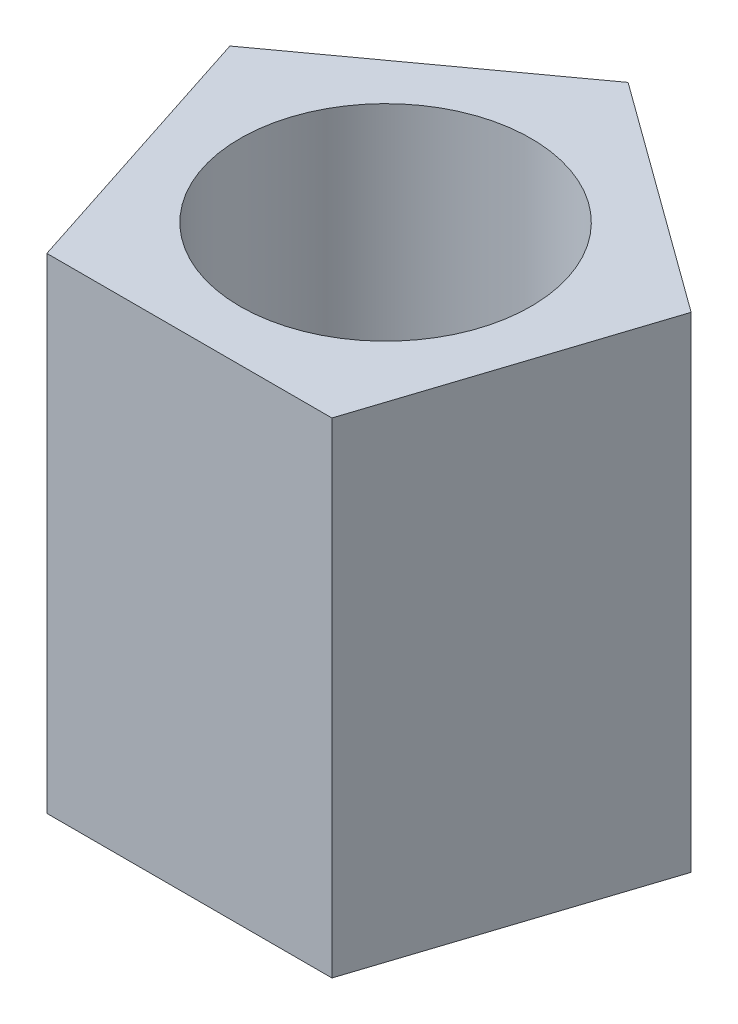
SolidWorks part; units mm, degrees
ref_plane "Front Plane" through (0, 0, 0) normal (0, 0, 1) x (1, 0, 0)
ref_plane "Top Plane" through (0, 0, 0) normal (0, 1, 0) x (1, 0, 0)
ref_plane "Right Plane" through (0, 0, 0) normal (1, 0, 0) x (0, 0, -1)
sketch "Sketch1" plane through (0, 0, 0) normal (0, 1, 0) x (1, 0, 0)
  line L0 (0, 0) -> (0, 6.35) construction
  line L1 (0, 0) -> (6.0392, 1.9623) construction
  line L2 (0, 6.35) -> (6.0392, 1.9623)
  line L3 (0, 6.35) -> (0, 0)
  line L4 (0, 0) -> (6.0392, 1.9623)
  circle A0 centre (0, 0) radius 6.35 construction
  dimension "D2" = 72
sketch "Sketch2" plane through (0, 0, 0) normal (0, 0, 1) x (1, 0, 0)
  line L0 (0, 0) -> (0, 12.7) construction
ref_plane "Plane1" through (0, 12.7, 0) normal (0, 1, 0) x (1, 0, 0)
extrude "Boss-Extrude1" add sketch "Sketch1" along normal up to surface (12.7 mm away) contours L4 L2 L3 up to plane "Plane1"
pattern_circular "CirPattern1" count 5 over 360 about axis through (0, 0, 0) along (0, 1, 0) of "Boss-Extrude1"
sketch "Sketch3" plane through (0, 12.7, 0) normal (0, 1, 0) x (1, 0, 0)
  circle A0 centre (0, 0) radius 3.81
  dimension "D1" = 7.62
extrude "Cut-Extrude1" cut sketch "Sketch3" against normal through all
equation "\"Number of sides\"=5"
equation "\"Diameter\"=0.5"
equation "\"Height\"=0.5"
equation "\"D1@Sketch1\"=\"Diameter\""
equation "\"D2@Sketch1\"=360/\"Number of sides\""
equation "\"D1@Sketch2\"=\"Height\""
equation "\"D1@CirPattern1\"=\"Number of sides\""
equation "\"D1@Sketch3\"=\"Diameter\"*0.6"
